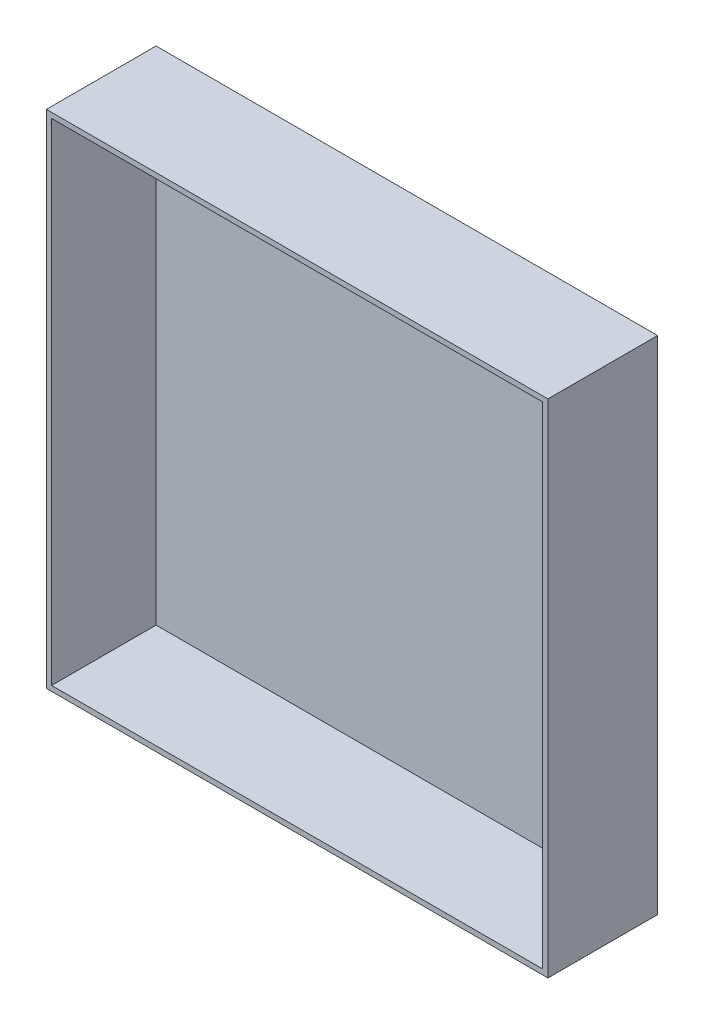
SolidWorks part; units mm, degrees
ref_plane "Front Plane" through (0, 0, 0) normal (0, 0, 1) x (1, 0, 0)
ref_plane "Top Plane" through (0, 0, 0) normal (0, 1, 0) x (1, 0, 0)
ref_plane "Right Plane" through (0, 0, 0) normal (1, 0, 0) x (0, 0, -1)
sketch "Sketch1" plane through (0, 0, 0) normal (0, 0, 1) x (1, 0, 0)
  line L1 (0, 0) -> (304.8, 0)
  line L2 (0, 0) -> (0, 304.8)
  line L3 (0, 304.8) -> (304.8, 304.8)
  line L4 (304.8, 0) -> (304.8, 304.8)
  dimension "D1" = 304.8
  dimension "D2" = 304.8
extrude "Boss-Extrude1" add sketch "Sketch1" along normal blind 3.175
sketch "Sketch2" plane through (0, 0, 3.175) normal (0, 0, 1) x (1, 0, 0)
  line L0 (0, 304.8) -> (0, 0) construction
  line L1 (304.8, 304.8) -> (0, 304.8)
  line L2 (304.8, 304.8) -> (304.8, 301.625)
  line L3 (304.8, 301.625) -> (0, 301.625)
  line L4 (0, 304.8) -> (0, 301.625)
  line L6 (0, 0) -> (3.175, 0)
  line L7 (0, 0) -> (0, 301.625)
  line L8 (0, 301.625) -> (3.175, 301.625)
  line L9 (3.175, 0) -> (3.175, 301.625)
  line L10 (304.8, 0) -> (301.625, 0)
  line L11 (304.8, 0) -> (304.8, 301.625)
  line L12 (304.8, 301.625) -> (301.625, 301.625)
  line L13 (301.625, 0) -> (301.625, 301.625)
  line L14 (3.175, 0) -> (301.625, 0)
  line L15 (3.175, 0) -> (3.175, 3.175)
  line L16 (3.175, 3.175) -> (301.625, 3.175)
  line L17 (301.625, 0) -> (301.625, 3.175)
  line M3 (0, 304.8) -> (0, 0)
  line M4 (0, 0) -> (304.8, 0)
  line M5 (304.8, 0) -> (304.8, 304.8)
  line M6 (304.8, 304.8) -> (0, 304.8)
  dimension "D1" = 3.175
  dimension "D2" = 3.175
  dimension "D3" = 3.175
  dimension "D4" = 3.175
extrude "Boss-Extrude2" add sketch "Sketch2" along normal blind 63.5 contours L16 L9 L13 M4 | L9 L3 M4 M3 | L3 M5 M6 M3 | L13 L3 M4 M5
